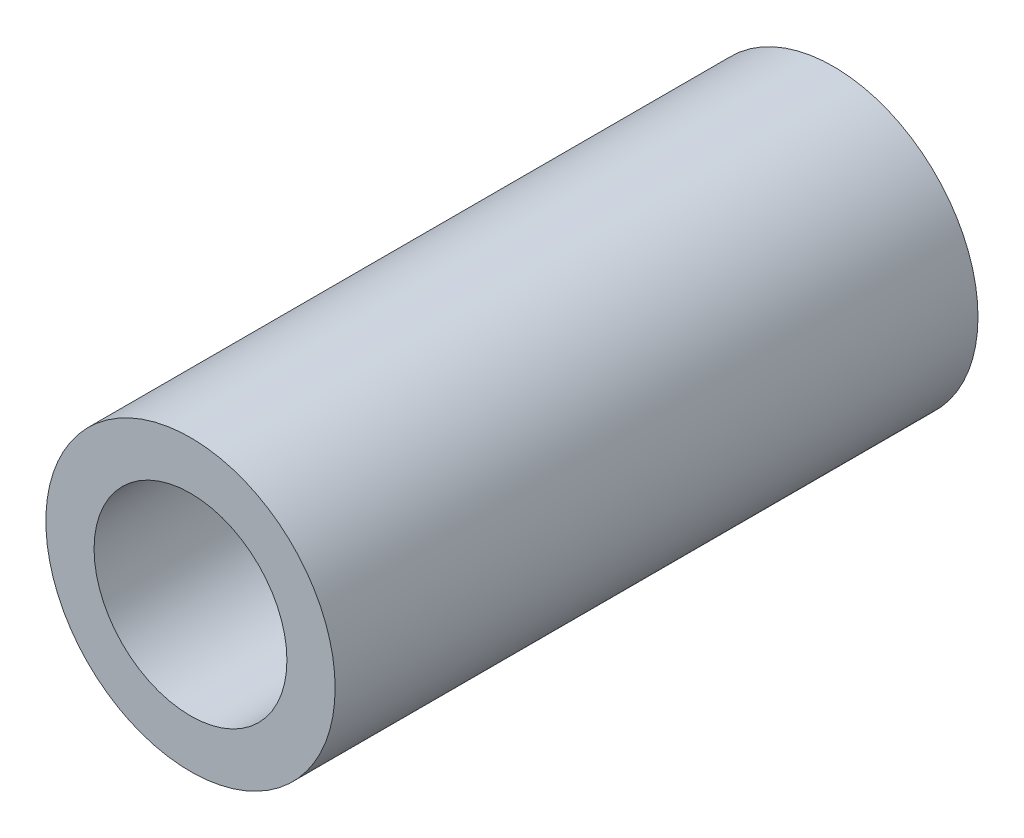
SolidWorks part; units mm, degrees
ref_plane "前视基准面" through (0, 0, 0) normal (0, 0, 1) x (1, 0, 0)
ref_plane "上视基准面" through (0, 0, 0) normal (0, 1, 0) x (1, 0, 0)
ref_plane "右视基准面" through (0, 0, 0) normal (1, 0, 0) x (0, 0, -1)
sketch "草图1" plane through (0, 0, 0) normal (0, 0, 1) x (1, 0, 0)
  circle A0 centre (0, 0) radius 4.5
  dimension "D1" = 9
extrude "凸台-拉伸1" add sketch "草图1" along normal blind 20 contours A0
sketch "草图2" plane through (0, 0, 0) normal (0, 0, -1) x (-1, 0, 0)
  circle A0 centre (0, 0) radius 3
  dimension "D1" = 6
extrude "切除-拉伸1" cut sketch "草图2" against normal through all contours A0
